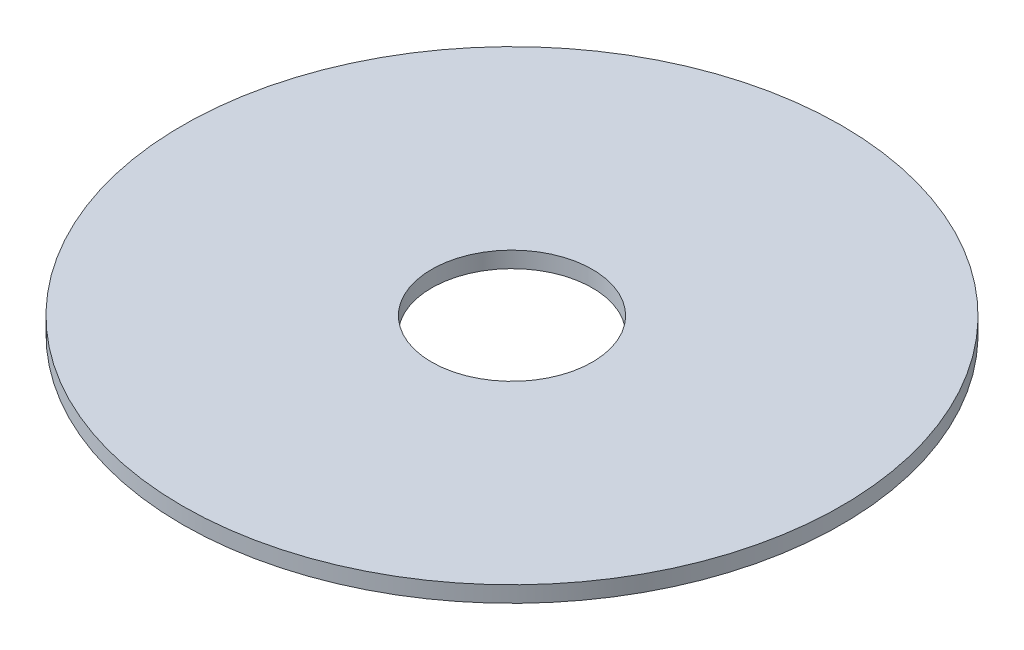
SolidWorks part; units mm, degrees
ref_plane "Front Plane" through (0, 0, 0) normal (0, 0, 1) x (1, 0, 0)
ref_plane "Top Plane" through (0, 0, 0) normal (0, 1, 0) x (1, 0, 0)
ref_plane "Right Plane" through (0, 0, 0) normal (1, 0, 0) x (0, 0, -1)
sketch "Sketch1" plane through (0, 0, 0) normal (0, 1, 0) x (1, 0, 0)
  circle A0 centre (0, 0) radius 41
  circle A1 centre (0, 0) radius 10
  dimension "D1" = 20
  dimension "D2" = 82
extrude "Boss-Extrude1" add sketch "Sketch1" along normal blind 2
